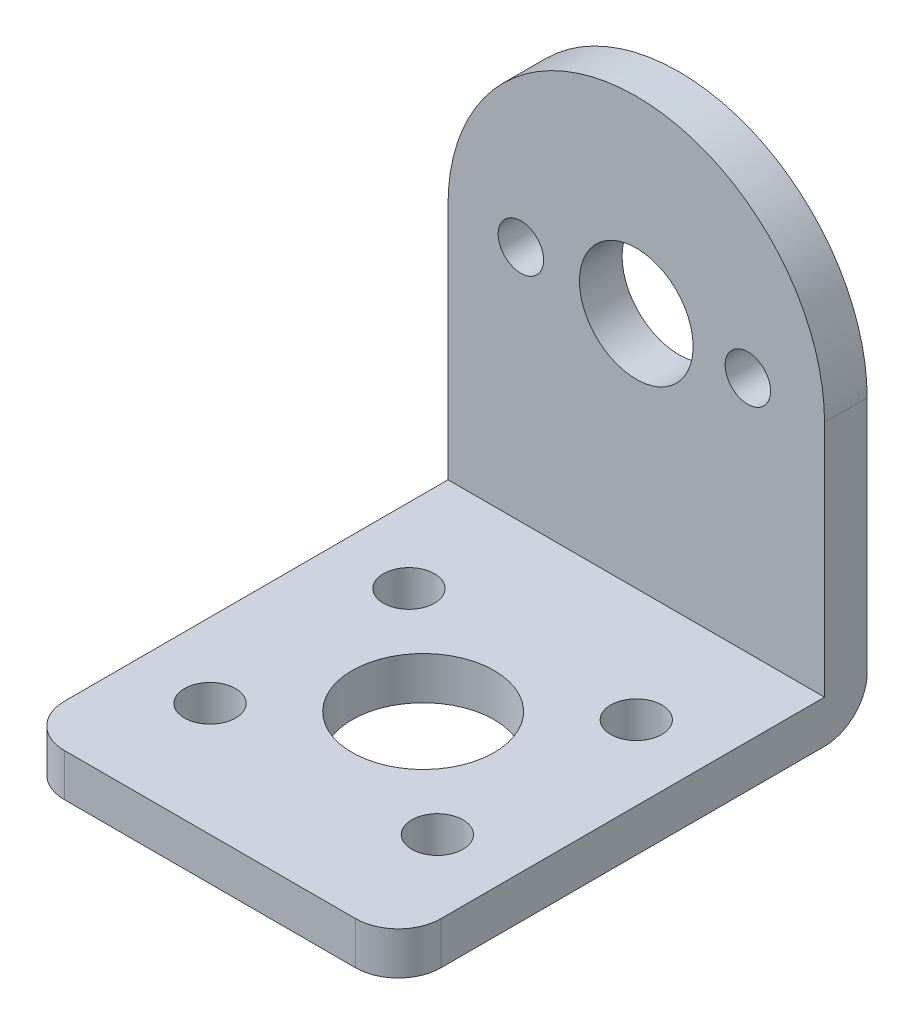
SolidWorks part; units mm, degrees
ref_plane "前视基准面" through (0, 0, 0) normal (0, 0, 1) x (1, 0, 0)
ref_plane "上视基准面" through (0, 0, 0) normal (0, 1, 0) x (1, 0, 0)
ref_plane "右视基准面" through (0, 0, 0) normal (1, 0, 0) x (0, 0, -1)
sketch "草图1" plane through (0, 0, 0) normal (0, 0, 1) x (1, 0, 0)
  line L1 (13.25, 0) -> (13.25, -19.75)
  line L2 (13.25, -19.75) -> (-13.25, -19.75)
  line L3 (-13.25, -19.75) -> (-13.25, 0)
  arc A0 (13.25, 0) -> (-13.25, 0) centre (0, 0) ccw
extrude "凸台-拉伸1" add sketch "草图1" along normal blind 3
sketch "草图2" plane through (0, 0, 3) normal (0, 0, 1) x (1, 0, 0)
  line L0 (-13.25, -16.75) -> (13.25, -16.75)
  line L1 (-13.25, 0) -> (-13.25, -19.75) construction
  line L2 (13.25, -19.75) -> (13.25, 0) construction
  line L3 (-13.25, -19.75) -> (13.25, -19.75) construction
  line L7 (-13.25, 0) -> (-13.25, -19.75)
  line L8 (-13.25, -19.75) -> (13.25, -19.75)
  line L9 (13.25, -19.75) -> (13.25, 0)
  line L10 (-13.25, -16.75) -> (-13.25, -19.75)
  line L11 (-13.25, -19.75) -> (13.25, -19.75)
  line L12 (13.25, -19.75) -> (13.25, -16.75)
  arc A1 (13.25, 0) -> (-13.25, 0) centre (0, 0) ccw
  dimension "D1" = 3
  dimension "D2" = 0
extrude "凸台-拉伸2" add sketch "草图2" along normal blind 30
fillet "圆角1" radius 3 1 edges at (0, -19.75, 0)
fillet "圆角2" radius 3 2 edges at (-13.25, -18.25, 33) (13.25, -18.25, 33)
sketch "草图3" plane through (0, 0, 0) normal (0, 0, -1) x (-1, 0, 0)
  circle A0 centre (0, 0) radius 4
extrude "切除-拉伸1" cut sketch "草图3" against normal through all both and the other way through all
sketch "草图4" plane through (0, 0, 0) normal (0, 0, -1) x (-1, 0, 0)
  circle A0 centre (8.121, 0) radius 1.6
  circle A1 centre (-7.8518, 0) radius 1.6
extrude "切除-拉伸2" cut sketch "草图4" against normal through all both and the other way through all
sketch "草图5" plane through (0, -19.75, 0) normal (0, -1, 0) x (-1, 0, 0)
  line L0 (10.25, -33) -> (-10.25, -33) construction
  circle A0 centre (0, -18) radius 5
  dimension "D1" = 15
extrude "切除-拉伸3" cut sketch "草图5" against normal through all both and the other way through all
sketch "草图6" plane through (0, -19.75, 0) normal (0, -1, 0) x (-1, 0, 0)
  line L0 (13.25, -3) -> (-13.25, -3) construction
  line L1 (-13.25, -30) -> (-13.25, -3) construction
  circle A0 centre (-8, -11) radius 1.8
  circle A1 centre (8, -11) radius 1.8
  circle A2 centre (8, -25) radius 1.8
  circle A3 centre (-8, -25) radius 1.8
  dimension "D1" = 8
  dimension "D2" = 5.25
  dimension "D3" = 16
  dimension "D4" = 14
extrude "切除-拉伸4" cut sketch "草图6" against normal through all both and the other way through all
